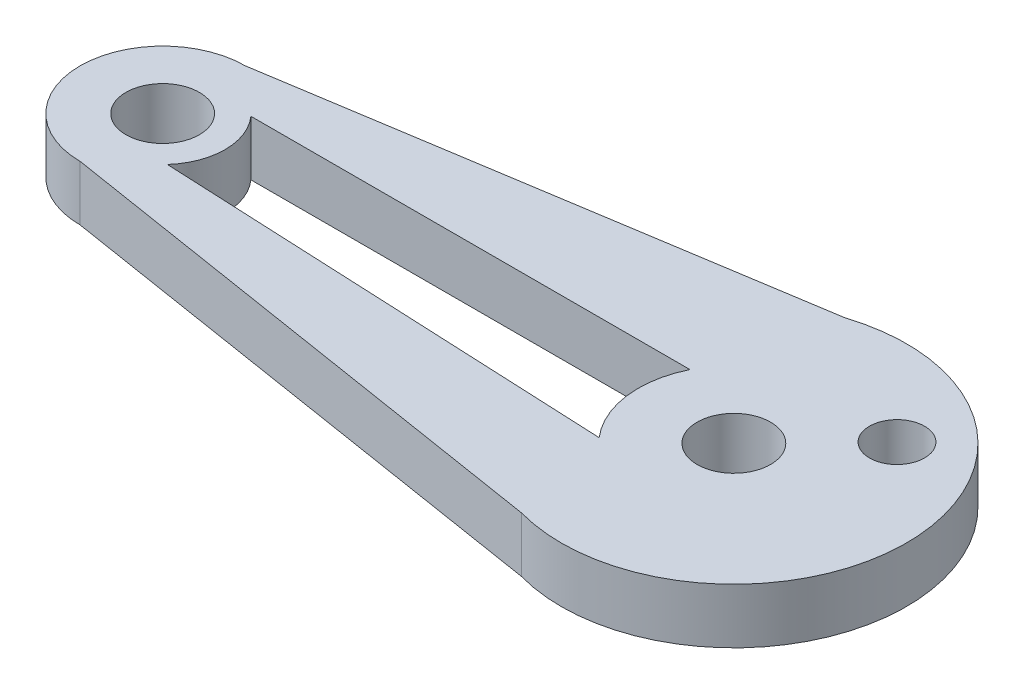
SolidWorks part; units mm, degrees
ref_plane "Front Plane" through (0, 0, 0) normal (0, 0, 1) x (1, 0, 0)
ref_plane "Top Plane" through (0, 0, 0) normal (0, 1, 0) x (1, 0, 0)
ref_plane "Right Plane" through (0, 0, 0) normal (1, 0, 0) x (0, 0, -1)
sketch "Sketch1" plane through (0, 0, 0) normal (0, 1, 0) x (1, 0, 0)
  line L0 (-51.7302, -5.0027) -> (-23.5205, -0.5581)
  line L1 (-51.7302, -14.0027) -> (-23.1302, -18.5642)
  line L2 (-51.7302, -9.5027) -> (-20.6302, -9.5027) construction
  line L3 (-49.202, -7.2293) -> (-25.302, -7.2194)
  line L4 (-49.202, -11.7762) -> (-24.5646, -12.9027)
  arc A0 (-51.7302, -5.0027) -> (-51.7302, -14.0027) centre (-51.7302, -9.5027) ccw
  circle A1 centre (-20.6302, -9.5027) radius 2
  arc A2 (-23.1302, -18.5642) -> (-23.5205, -0.5581) centre (-20.6302, -9.5027) ccw
  circle A3 centre (-51.7302, -9.5027) radius 2
  arc A4 (-49.202, -11.7762) -> (-49.202, -7.2293) centre (-51.7302, -9.5027) ccw
  arc A5 (-25.302, -7.2194) -> (-24.5646, -12.9027) centre (-20.6302, -9.5027) ccw
  circle A6 centre (-16.247, -5.0027) radius 1.5
  dimension "D1" = 9
  dimension "D2" = 18.8
  dimension "D3" = 4
  dimension "D5" = 4
  dimension "D6" = 6.8
  dimension "D7" = 10.4
  dimension "D10" = 3
  dimension "D4" = 31.1
  dimension "D8" = 28.6
  dimension "D9" = 23.9
extrude "Boss-Extrude1" add sketch "Sketch1" along normal blind 3
